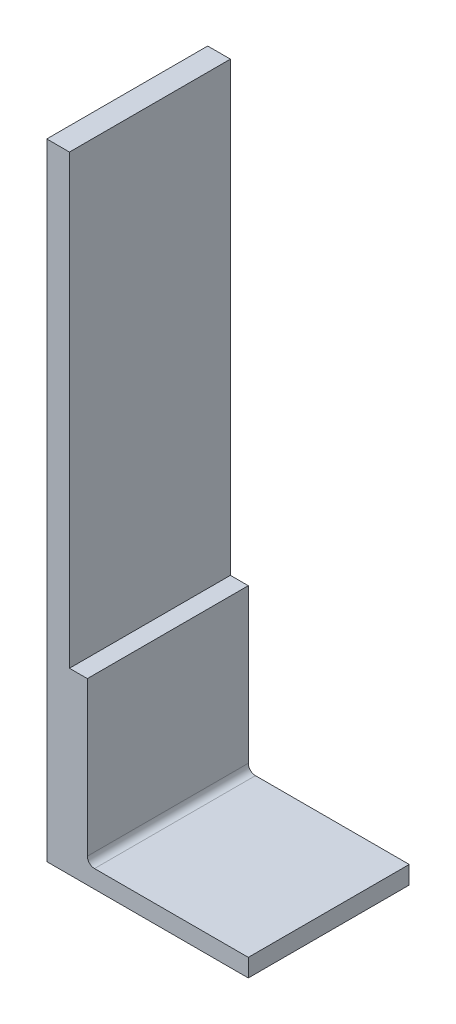
SolidWorks part; units mm, degrees
material "Aleación 1060"
ref_plane "Alzado" through (0, 0, 0) normal (0, 0, 1) x (1, 0, 0)
ref_plane "Planta" through (0, 0, 0) normal (0, 1, 0) x (1, 0, 0)
ref_plane "Vista lateral" through (0, 0, 0) normal (1, 0, 0) x (0, 0, -1)
sketch "Croquis1" plane through (0, 0, 0) normal (0, 0, 1) x (1, 0, 0)
  line L0 (0, 0) -> (0, 100)
  line L1 (0, 0) -> (100, 0)
  line L2 (10, 14) -> (10, 100)
  line L3 (14, 10) -> (100, 10)
  line L4 (0, 100) -> (10, 100)
  line L5 (100, 0) -> (100, 10)
  line L6 (10, 10) -> (10, 100) construction
  line L7 (10, 10) -> (100, 10) construction
  arc A0 (10, 14) -> (14, 10) centre (14, 14) ccw
  dimension "D2" = 4
  dimension "D1" = 10
extrude "Saliente-Extruir1" add sketch "Croquis1" along normal blind 90
sketch "Croquis2" plane through (0, 0, 0) normal (-1, 0, 0) x (0, 0, 1)
  line L1 (0, 0) -> (90, 0)
  line L2 (0, 0) -> (0, 350)
  line L3 (0, 350) -> (90, 350)
  line L4 (90, 0) -> (90, 350)
  dimension "D1" = 350
  dimension "D2" = 90
extrude "Saliente-Extruir2" add sketch "Croquis2" along normal blind 12.7
